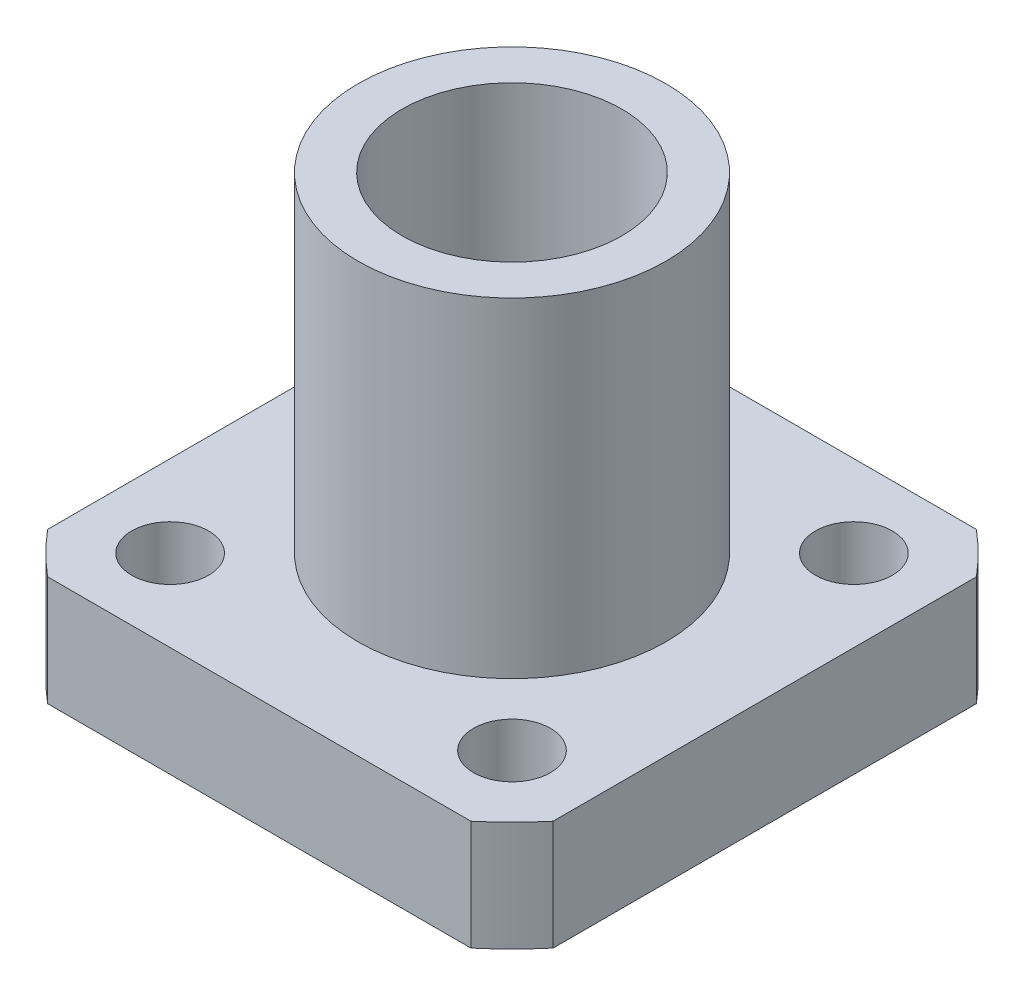
SolidWorks part; units mm, degrees
material "AISI 304"
ref_plane "Front Plane" through (0, 0, 0) normal (0, 0, 1) x (1, 0, 0)
ref_plane "Top Plane" through (0, 0, 0) normal (0, 1, 0) x (1, 0, 0)
ref_plane "Right Plane" through (0, 0, 0) normal (1, 0, 0) x (0, 0, -1)
sketch "Sketch1" plane through (0, 0, 0) normal (0, 1, 0) x (1, 0, 0)
  line L0 (-41.1814, 0) -> (34.986, 0) construction
  line L1 (0, 27.4847) -> (0, -27.5454) construction
  line L3 (-9.6307, -11.5) -> (9.6307, -11.5)
  line L4 (-11.5, -9.6307) -> (-11.5, 9.6307)
  line L5 (-9.6307, 11.5) -> (9.6307, 11.5)
  line L6 (11.5, -9.6307) -> (11.5, 9.6307)
  line L7 (-11.5, -11.5) -> (11.5, 11.5) construction
  line L8 (-11.5, 11.5) -> (11.5, -11.5) construction
  arc A0 (-9.6307, 11.5) -> (-11.5, 9.6307) centre (0, 0) ccw
  arc A1 (11.5, 9.6307) -> (9.6307, 11.5) centre (0, 0) ccw
  arc A2 (9.6307, -11.5) -> (11.5, -9.6307) centre (0, 0) ccw
  arc A3 (-11.5, -9.6307) -> (-9.6307, -11.5) centre (0, 0) ccw
  circle A4 centre (0, 0) radius 11 construction
  circle A5 centre (-7.7782, 7.7782) radius 1.75
  circle A6 centre (7.7782, 7.7782) radius 1.75
  circle A7 centre (-7.7782, -7.7782) radius 1.75
  circle A8 centre (7.7782, -7.7782) radius 1.75
  dimension "D1" = 30
  dimension "D8" = 22
  dimension "D11" = 3.5
  dimension "D12" = 3.5
  dimension "D13" = 3.5
  dimension "D14" = 3.5
  dimension "D2" = 23
  dimension "D3" = 23
  dimension "D4" = 11.5
  dimension "D5" = 11.5
  dimension "D6" = 11.5
  dimension "D7" = 11.5
  dimension "D9" = 45
  dimension "D10" = 45
extrude "Boss-Extrude1" add sketch "Sketch1" along normal blind 5
sketch "Sketch2" plane through (0, 5, 0) normal (0, 1, 0) x (1, 0, 0)
  circle A0 centre (0, 0) radius 7
  dimension "D1" = 14
extrude "Boss-Extrude2" add sketch "Sketch2" along normal blind 15
sketch "Sketch3" plane through (0, 20, 0) normal (0, 1, 0) x (1, 0, 0)
  circle A0 centre (0, 0) radius 5
  dimension "D1" = 10
extrude "Cut-Extrude1" cut sketch "Sketch3" against normal through all
